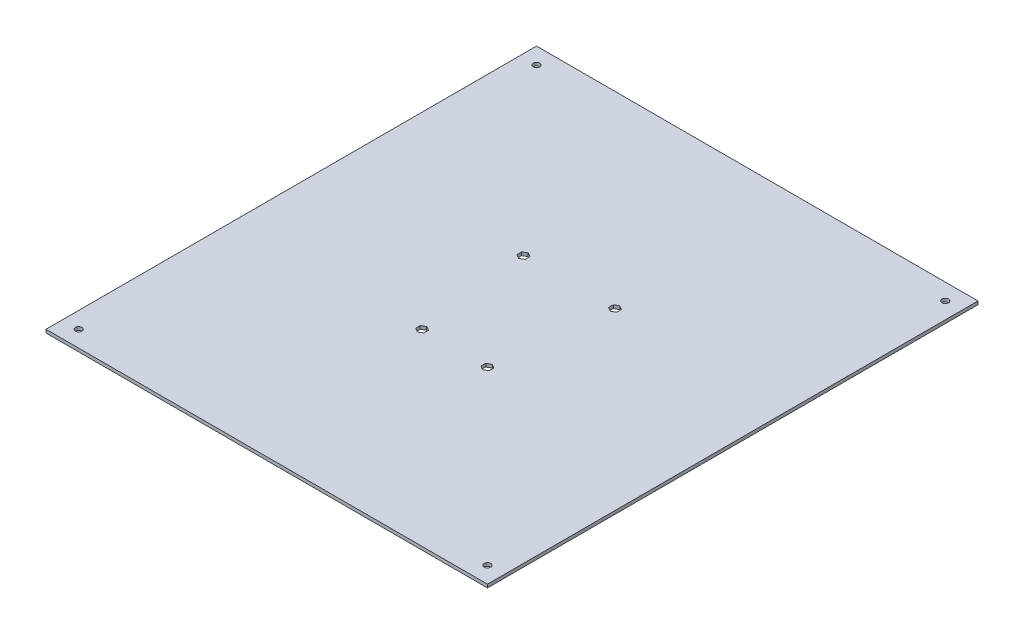
SolidWorks part; units mm, degrees
ref_plane "Front Plane" through (0, 0, 0) normal (0, 0, 1) x (1, 0, 0)
ref_plane "Top Plane" through (0, 0, 0) normal (0, 1, 0) x (1, 0, 0)
ref_plane "Right Plane" through (0, 0, 0) normal (1, 0, 0) x (0, 0, -1)
sketch "Sketch1" plane through (0, 0, 0) normal (0, 1, 0) x (1, 0, 0)
  line L1 (0, 0) -> (270, 0)
  line L2 (0, 0) -> (0, 300)
  line L3 (0, 300) -> (270, 300)
  line L4 (270, 0) -> (270, 300)
  circle A0 centre (10, 290) radius 2
  circle A1 centre (10, 10) radius 2
  circle A2 centre (260, 10) radius 2
  circle A3 centre (260, 290) radius 2
extrude "Boss-Extrude1" add sketch "Sketch1" along normal blind 2
sketch "Sketch2" plane through (0, 2, 0) normal (0, 1, 0) x (1, 0, 0)
  line L4 (109.5, 185) -> (109.5005, 185)
  line L5 (117.5, 115) -> (117.5008, 115)
  line L6 (152.4992, 115) -> (152.5, 115)
  line L7 (162.9451, 182.1138) -> (165.4721, 183.5093)
  line L8 (165.4721, 183.5093) -> (165.527, 186.3956)
  line L9 (165.527, 186.3956) -> (163.0549, 187.8862)
  line L10 (163.0549, 187.8862) -> (160.5279, 186.4907)
  line L11 (160.5279, 186.4907) -> (160.473, 183.6044)
  line L12 (160.473, 183.6044) -> (162.9451, 182.1138)
  line L13 (154.9259, 112.1142) -> (157.4621, 113.493)
  line L14 (157.4621, 113.493) -> (157.5362, 116.3788)
  line L15 (157.5362, 116.3788) -> (155.0741, 117.8858)
  line L16 (155.0741, 117.8858) -> (152.5379, 116.507)
  line L17 (152.5379, 116.507) -> (152.4638, 113.6212)
  line L18 (152.4638, 113.6212) -> (154.9259, 112.1142)
  line L19 (115.0741, 112.1142) -> (117.5362, 113.6212)
  line L20 (117.5362, 113.6212) -> (117.4621, 116.507)
  line L21 (117.4621, 116.507) -> (114.9259, 117.8858)
  line L22 (114.9259, 117.8858) -> (112.4638, 116.3788)
  line L23 (112.4638, 116.3788) -> (112.5379, 113.493)
  line L24 (112.5379, 113.493) -> (115.0741, 112.1142)
  line L25 (107.0549, 182.1138) -> (109.527, 183.6044)
  line L26 (109.527, 183.6044) -> (109.4721, 186.4907)
  line L27 (109.4721, 186.4907) -> (106.9451, 187.8862)
  line L28 (106.9451, 187.8862) -> (104.473, 186.3956)
  line L29 (104.473, 186.3956) -> (104.5279, 183.5093)
  line L30 (104.5279, 183.5093) -> (107.0549, 182.1138)
  line L31 (160.4995, 185) -> (160.5, 185)
  circle A0 centre (163, 185) radius 2.5 construction
  circle A1 centre (155, 115) radius 2.5 construction
  circle A2 centre (115, 115) radius 2.5 construction
  circle A3 centre (107, 185) radius 2.5 construction
  point P9 (135, 150)
extrude "Cut-Extrude1" cut sketch "Sketch2" against normal blind 145
